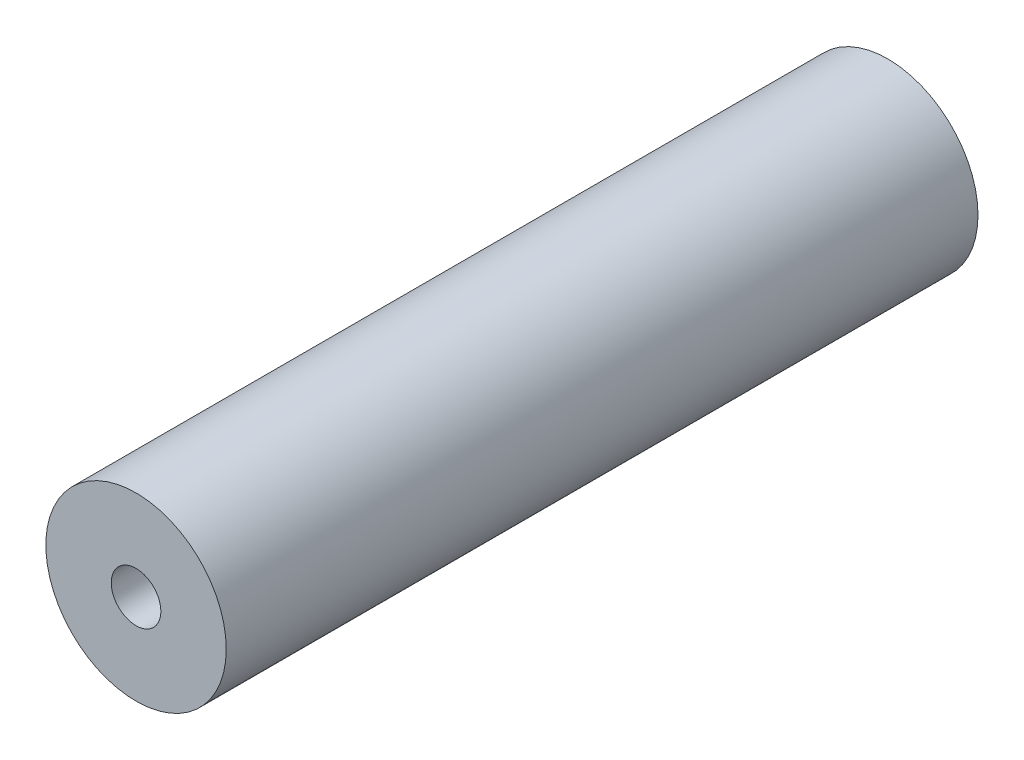
SolidWorks part; units mm, degrees
ref_plane "Спереди" through (0, 0, 0) normal (0, 0, 1) x (1, 0, 0)
ref_plane "Сверху" through (0, 0, 0) normal (0, 1, 0) x (1, 0, 0)
ref_plane "Справа" through (0, 0, 0) normal (1, 0, 0) x (0, 0, -1)
sketch "Эскиз1" plane through (0, 0, 0) normal (0, 0, 1) x (1, 0, 0)
  circle A0 centre (0, 0) radius 6
  dimension "D1" = 12
extrude "Бобышка-Вытянуть1" add sketch "Эскиз1" along normal blind 50
sketch "Эскиз2" plane through (0, 0, 50) normal (0, 0, 1) x (1, 0, 0)
  circle A0 centre (0, 0) radius 1.65
  dimension "D1" = 3.3
extrude "Вырез-Вытянуть1" cut sketch "Эскиз2" against normal blind 15
sketch "Эскиз5" plane through (0, 0, 0) normal (0, 0, -1) x (-1, 0, 0)
  circle A0 centre (0, 0) radius 1.65
  dimension "D1" = 3.3
extrude "Вырез-Вытянуть2" cut sketch "Эскиз5" against normal blind 15
